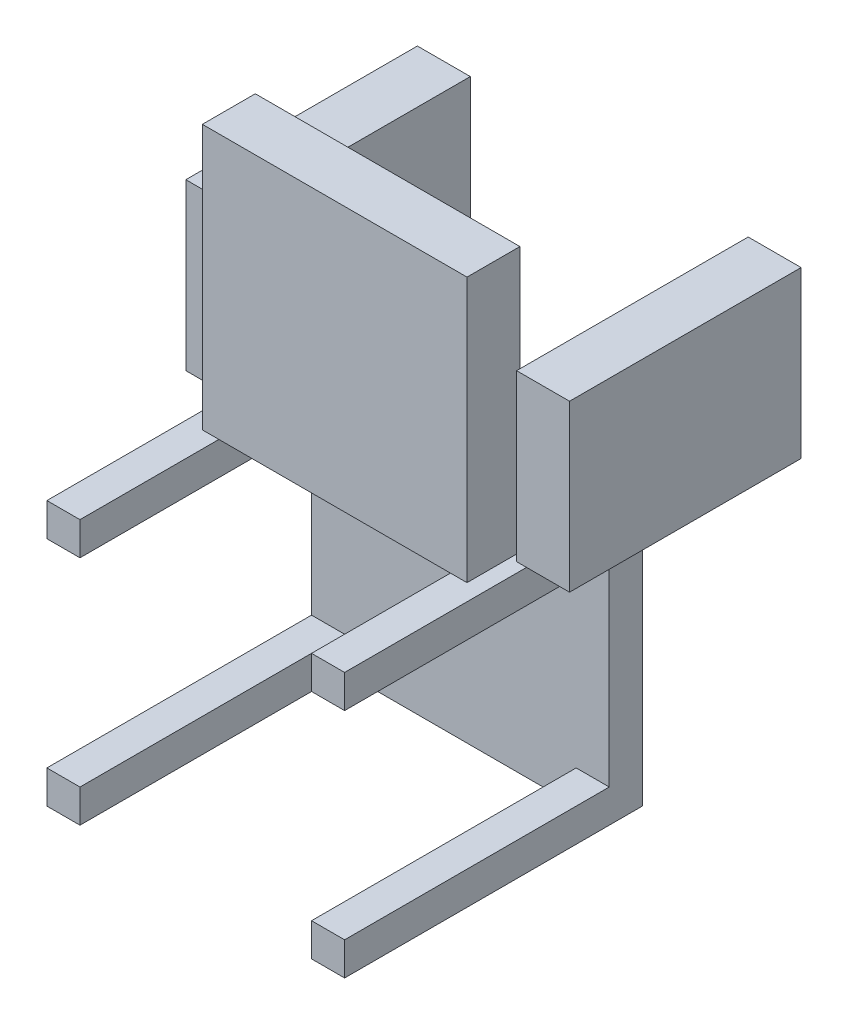
SolidWorks part; units mm, degrees
ref_plane "前视基准面" through (0, 0, 0) normal (0, 0, 1) x (1, 0, 0)
ref_plane "上视基准面" through (0, 0, 0) normal (0, 1, 0) x (1, 0, 0)
ref_plane "右视基准面" through (0, 0, 0) normal (1, 0, 0) x (0, 0, -1)
other "Configuration Table"
sketch "草图1" plane through (0, 0, 0) normal (0, 0, 1) x (1, 0, 0)
  line L1 (-225, -200) -> (225, -200)
  line L2 (-225, -200) -> (-225, 200)
  line L3 (-225, 200) -> (225, 200)
  line L4 (225, -200) -> (225, 200)
  line L5 (-225, -200) -> (225, 200) construction
  line L6 (-225, 200) -> (225, -200) construction
  point P0 (0, 0)
extrude "凸台-拉伸1" add sketch "草图1" along normal blind 50
sketch "草图2" plane through (0, 0, 0) normal (0, 0, 1) x (1, 0, 0)
  line L1 (-225, -200) -> (-175, -200)
  line L2 (-225, -200) -> (-225, -150)
  line L3 (-225, -150) -> (-175, -150)
  line L4 (-175, -200) -> (-175, -150)
  line L5 (-225, -200) -> (-175, -150) construction
  line L6 (-225, -150) -> (-175, -200) construction
  point P0 (-200, -175)
extrude "凸台-拉伸2" add sketch "草图2" along normal blind 450
sketch "草图3" plane through (0, 0, 0) normal (0, 0, 1) x (1, 0, 0)
  line L0 (225, -200) -> (225, 200) construction
  line L1 (175, -200) -> (225, -200)
  line L2 (175, -200) -> (175, -150)
  line L3 (175, -150) -> (225, -150)
  line L4 (225, -200) -> (225, -150)
  line L5 (175, -200) -> (225, -150) construction
  line L6 (175, -150) -> (225, -200) construction
  point P0 (200, -175)
extrude "凸台-拉伸3" add sketch "草图3" along normal blind 450
sketch "草图4" plane through (0, 0, 0) normal (0, 0, 1) x (1, 0, 0)
  line L0 (225, 200) -> (-225, 200) construction
  line L1 (-225, 150) -> (-175, 150)
  line L2 (-225, 150) -> (-225, 200)
  line L3 (-225, 200) -> (-175, 200)
  line L4 (-175, 150) -> (-175, 200)
  line L5 (-225, 150) -> (-175, 200) construction
  line L6 (-225, 200) -> (-175, 150) construction
  point P0 (-200, 175)
extrude "凸台-拉伸4" add sketch "草图4" along normal blind 450
sketch "草图5" plane through (0, 0, 0) normal (0, 0, 1) x (1, 0, 0)
  line L1 (175, 150) -> (225, 150)
  line L2 (175, 150) -> (175, 200)
  line L3 (175, 200) -> (225, 200)
  line L4 (225, 150) -> (225, 200)
  line L5 (175, 150) -> (225, 200) construction
  line L6 (175, 200) -> (225, 150) construction
  point P0 (200, 175)
extrude "凸台-拉伸5" add sketch "草图5" along normal blind 450
sketch "草图6" plane through (0, 200, 0) normal (0, 1, 0) x (1, 0, 0)
  line L1 (-200, -240) -> (200, -240)
  line L2 (-200, -240) -> (-200, -160)
  line L3 (-200, -160) -> (200, -160)
  line L4 (200, -240) -> (200, -160)
  line L5 (-200, -240) -> (200, -160) construction
  line L6 (-200, -160) -> (200, -240) construction
  point P0 (0, -200)
extrude "凸台-拉伸6" add sketch "草图6" along normal blind 400
sketch "草图7" plane through (0, 200, 0) normal (0, 1, 0) x (1, 0, 0)
  line L1 (-290, -175) -> (-210, -175)
  line L2 (-290, -175) -> (-290, 175)
  line L3 (-290, 175) -> (-210, 175)
  line L4 (-210, -175) -> (-210, 175)
  line L5 (-290, -175) -> (-210, 175) construction
  line L6 (-290, 175) -> (-210, -175) construction
  point P0 (-250, 0)
extrude "凸台-拉伸7" add sketch "草图7" along normal blind 250
sketch "草图8" plane through (0, 200, 0) normal (0, 1, 0) x (1, 0, 0)
  line L1 (210, -175) -> (290, -175)
  line L2 (210, -175) -> (210, 175)
  line L3 (210, 175) -> (290, 175)
  line L4 (290, -175) -> (290, 175)
  line L5 (210, -175) -> (290, 175) construction
  line L6 (210, 175) -> (290, -175) construction
  point P0 (250, 0)
extrude "凸台-拉伸8" add sketch "草图8" along normal blind 250
